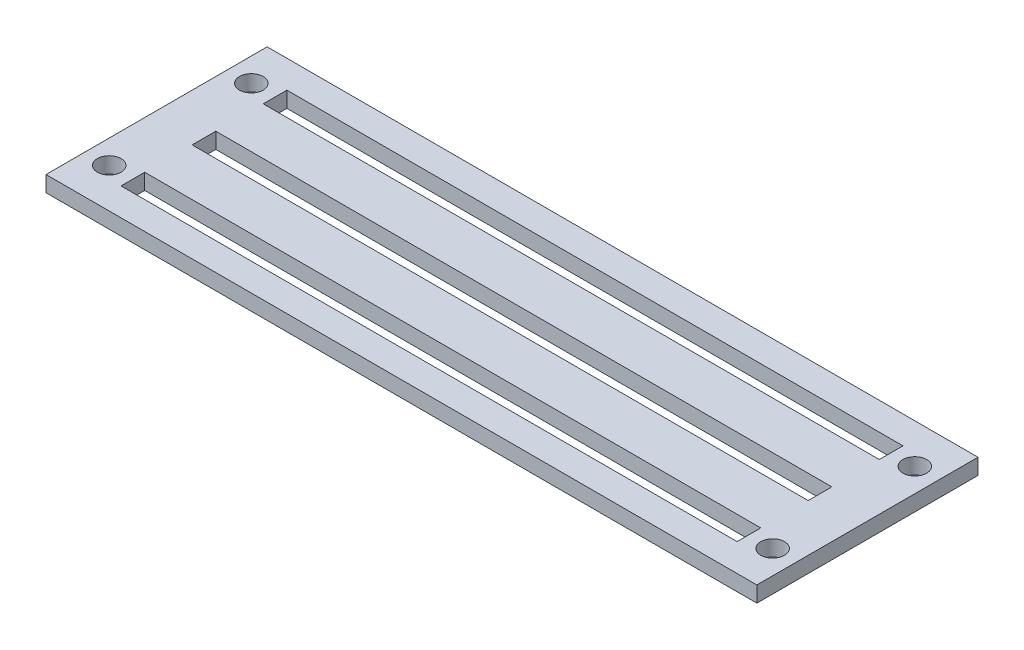
SolidWorks part; units mm, degrees
ref_plane "Front Plane" through (0, 0, 0) normal (0, 0, 1) x (1, 0, 0)
ref_plane "Top Plane" through (0, 0, 0) normal (0, 1, 0) x (1, 0, 0)
ref_plane "Right Plane" through (0, 0, 0) normal (1, 0, 0) x (0, 0, -1)
sketch "Sketch1" plane through (0, 0, 0) normal (0, 1, 0) x (1, 0, 0)
  line L1 (0, 0) -> (90, 0)
  line L2 (0, 0) -> (0, 28)
  line L3 (0, 28) -> (90, 28)
  line L4 (90, 0) -> (90, 28)
  dimension "D1" = 28
  dimension "D2" = 90
extrude "Boss-Extrude1" add sketch "Sketch1" along normal blind 2
sketch "Sketch2" plane through (0, 2, 0) normal (0, 1, 0) x (1, 0, 0)
  line L0 (0, 23) -> (90, 23) construction
  line L1 (0, 28) -> (0, 0) construction
  line L2 (90, 0) -> (90, 28) construction
  line L3 (6, 28) -> (6, 0) construction
  line L4 (90, 5) -> (0, 5) construction
  line L5 (6, 0) -> (84, 0) construction
  line L6 (90, 28) -> (0, 28) construction
  line L7 (0, 0) -> (90, 0) construction
  line L8 (3, 0) -> (87, 0) construction
  line L9 (84, 0) -> (84, 28) construction
  line L10 (0, 14) -> (90, 14) construction
  line L11 (6, 0) -> (84, 0) construction
  line L12 (6, 15.5) -> (84, 15.5)
  line L13 (6, 15.5) -> (6, 12.5)
  line L14 (6, 12.5) -> (84, 12.5)
  line L19 (84, 6.5) -> (6, 6.5)
  line L20 (84, 6.5) -> (84, 3.5)
  line L21 (84, 3.5) -> (6, 3.5)
  line L22 (6, 6.5) -> (6, 3.5)
  line L23 (6, 24.5) -> (84, 24.5)
  line L24 (6, 24.5) -> (6, 21.5)
  line L25 (6, 21.5) -> (84, 21.5)
  line L26 (84, 24.5) -> (84, 21.5)
  line L27 (84, 15.5) -> (84, 12.5)
  circle A0 centre (3, 23) radius 1.5
  circle A1 centre (3, 5) radius 1.5
  circle A3 centre (87, 23) radius 1.5
  circle A4 centre (87, 5) radius 1.5
  dimension "D5" = 3
  dimension "D6" = 3
  dimension "D7" = 3
  dimension "D8" = 3
  dimension "D2" = 5
  dimension "D3" = 5
  dimension "D4" = 3
  dimension "D9" = 1.5
  dimension "D10" = 3
  dimension "D11" = 1.5
  dimension "D12" = 3
  dimension "D13" = 1.5
extrude "Cut-Extrude1" cut sketch "Sketch2" against normal through all
